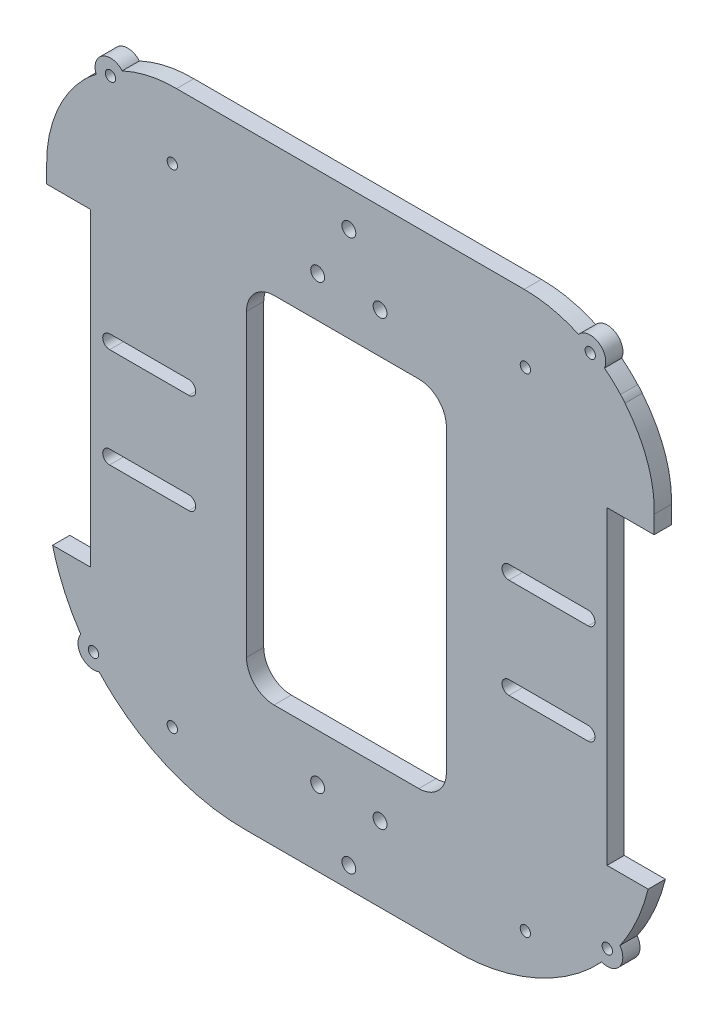
SolidWorks part; units mm, degrees
ref_plane "Front Plane" through (0, 0, 0) normal (0, 0, 1) x (1, 0, 0)
ref_plane "Top Plane" through (0, 0, 0) normal (0, 1, 0) x (1, 0, 0)
ref_plane "Right Plane" through (0, 0, 0) normal (1, 0, 0) x (0, 0, -1)
sketch "Sketch1" plane through (0, 0, 0) normal (0, 0, 1) x (1, 0, 0)
  line L0 (0.5046, 36.3194) -> (0.5046, -35.0114) construction
  line L1 (-23.6684, -1.9236) -> (30.8981, -1.9236) construction
  line L2 (47.0046, -13.9593) -> (70.0046, -13.9593) construction
  line L4 (20.8353, 50.5569) -> (-21.2253, 50.5569)
  line L6 (47.0046, -15.9593) -> (70.0046, -15.9593)
  line L7 (28.8353, 42.5569) -> (28.8353, -44.4755)
  line L10 (47.0046, -11.9593) -> (70.0046, -11.9593)
  line L13 (47.0046, 15.0407) -> (70.0046, 15.0407) construction
  line L16 (75.5046, -44.4593) -> (75.5046, 45.5407)
  line L17 (75.5046, -44.4593) -> (100.9515, -44.4593)
  line L18 (-74.4954, -44.4593) -> (-74.4954, 45.5407)
  line L19 (75.5046, 45.5407) -> (100.0597, 45.5407)
  line L21 (-74.4954, 45.5407) -> (-96.5901, 45.5407)
  line L22 (-74.4954, -44.4593) -> (-96.0698, -44.4593)
  line L23 (-45.9954, -13.9593) -> (-68.9954, -13.9593) construction
  line L24 (-45.9954, -15.9593) -> (-68.9954, -15.9593)
  line L25 (-45.9954, -11.9593) -> (-68.9954, -11.9593)
  line L26 (20.8353, -52.4755) -> (-21.2253, -52.4755)
  line L27 (-29.2253, 42.5569) -> (-29.2253, -44.4755)
  line L28 (-45.9954, 15.0407) -> (-68.9954, 15.0407) construction
  line L32 (41.4624, 99.173) -> (-37.9933, 99.173)
  line L33 (-96.0698, -44.4593) -> (-96.0698, -58.9411)
  line L34 (-57.1595, -97.8475) -> (62.0583, -97.8475)
  line L35 (100.9515, -58.9359) -> (100.9515, -44.4593)
  line L36 (-45.9954, 13.0407) -> (-68.9954, 13.0407)
  line L37 (-45.9954, 17.0407) -> (-68.9954, 17.0407)
  line L38 (47.0046, 13.0407) -> (70.0046, 13.0407)
  line L39 (47.0046, 17.0407) -> (70.0046, 17.0407)
  circle A0 centre (0.5046, -81.9236) radius 2.01
  circle A1 centre (-8.5604, -66.2225) radius 2.01
  circle A2 centre (9.5696, -66.2225) radius 2.01
  circle A3 centre (9.5696, 62.3754) radius 2.01
  circle A4 centre (-8.5604, 62.3754) radius 2.01
  circle A5 centre (0.5046, 78.0764) radius 2.01
  circle A6 centre (51.7877, 68.9682) radius 1.5
  circle A7 centre (-50.7786, 68.9682) radius 1.5
  circle A8 centre (-50.7786, -72.8153) radius 1.5
  circle A9 centre (51.7877, -72.8153) radius 1.5
  arc A18 (20.8353, 50.5569) -> (28.8353, 42.5569) centre (20.8353, 42.5569) cw
  arc A19 (28.8353, -44.4755) -> (20.8353, -52.4755) centre (20.8353, -44.4755) cw
  arc A20 (-21.2253, -52.4755) -> (-29.2253, -44.4755) centre (-21.2253, -44.4755) cw
  arc A21 (-21.2253, 50.5569) -> (-29.2253, 42.5569) centre (-21.2253, 42.5569) ccw
  arc A22 (-45.9954, -15.9593) -> (-45.9954, -11.9593) centre (-45.9954, -13.9593) ccw
  arc A23 (-68.9954, -11.9593) -> (-68.9954, -15.9593) centre (-68.9954, -13.9593) ccw
  arc A24 (-45.9954, 13.0407) -> (-45.9954, 17.0407) centre (-45.9954, 15.0407) ccw
  arc A25 (-68.9954, 17.0407) -> (-68.9954, 13.0407) centre (-68.9954, 15.0407) ccw
  arc A26 (47.0046, -15.9593) -> (47.0046, -11.9593) centre (47.0046, -13.9593) cw
  arc A27 (70.0046, -11.9593) -> (70.0046, -15.9593) centre (70.0046, -13.9593) cw
  arc A28 (47.0046, 13.0407) -> (47.0046, 17.0407) centre (47.0046, 15.0407) cw
  arc A29 (70.0046, 17.0407) -> (70.0046, 13.0407) centre (70.0046, 15.0407) cw
  spline S4 degree 3 poles (-37.9933, 99.173) (-41.8284, 99.1922) (-49.5281, 98.4356) (-60.5812, 95.0816) (-70.8089, 89.6705) (-79.8089, 82.3002) (-87.1478, 73.2755) (-92.6436, 63.0291) (-95.5634, 53.6011) (-96.4127, 47.6625) (-96.5901, 45.5407) knots 0.000115 0.000115 0.000115 0.000115 0.12506 0.250006 0.374952 0.499897 0.624843 0.749788 0.874734 0.943757 0.943757 0.943757 0.943757
  spline S5 degree 3 poles (-96.0698, -58.9411) (-96.1036, -60.2428) (-96.0208, -62.8642) (-95.2849, -67.9584) (-93.3689, -74.058) (-89.6962, -80.7285) (-84.8498, -86.585) (-79.0078, -91.4529) (-72.338, -95.1463) (-66.2226, -97.0712) (-61.1064, -97.8056) (-58.4686, -97.8842) (-57.1595, -97.8475) knots 0.000902 0.000902 0.000902 0.000902 0.063285 0.125668 0.250434 0.3752 0.499967 0.624733 0.749499 0.874265 0.936648 0.999031 0.999031 0.999031 0.999031
  spline S6 degree 3 poles (62.0583, -97.8475) (63.3493, -97.873) (65.9465, -97.7788) (71.0064, -97.0392) (77.08, -95.1471) (83.7477, -91.5254) (89.6215, -86.7311) (94.5168, -80.9234) (98.2368, -74.2556) (100.175, -68.1051) (100.9119, -62.9385) (100.9892, -60.2624) (100.9515, -58.9359) knots 0.000693 0.000693 0.000693 0.000693 0.06309 0.125486 0.250278 0.375071 0.499863 0.624656 0.749448 0.874241 0.936637 0.999033 0.999033 0.999033 0.999033
  spline S7 degree 3 poles (100.0597, 45.5407) (100.0418, 45.7543) (99.85, 47.8935) (98.9687, 53.8304) (96.1308, 63.0673) (90.671, 73.2777) (83.3411, 82.2625) (74.3661, 89.5939) (64.1648, 95.0502) (54.9283, 97.8853) (47.2878, 99.0202) (43.4004, 99.1912) (41.4624, 99.173) knots 0.055789 0.055789 0.055789 0.055789 0.062711 0.125183 0.250126 0.37507 0.500013 0.624957 0.7499 0.874844 0.937315 0.999787 0.999787 0.999787 0.999787
  point P11 (0.1732, 0.5407)
  point P12 (0.492, 0.5407)
  point P13 (0.1732, 0.5407)
  point P27 (58.5046, -13.9593)
  point P43 (1.739, 0.6627)
  point P45 (-57.4954, -13.9593)
  point P49 (58.5046, 15.0407)
  point P83 (-57.4954, 15.0407)
  dimension "D1" = 4.02
  dimension "D2" = 4.02
  dimension "D3" = 4.02
  dimension "D10" = 3
  dimension "D12" = 8
  dimension "D9" = 160
  dimension "D13" = 150
  dimension "D4" = 18.13
  dimension "D5" = 18.13
  dimension "D6" = 18.13
  dimension "D7" = 0
  dimension "D8" = 0
  dimension "D11" = 0
  dimension "D14" = 4
  dimension "D15" = 23
  dimension "D16" = 4
  dimension "D17" = 29
  dimension "D18" = 12.0358
  dimension "D19" = 23
  dimension "D20" = 17
  dimension "D21" = 17
extrude "Boss-Extrude1" add sketch "Sketch1" along normal blind 5
extrude "Cut-Extrude1" cut sketch "Sketch3" against normal blind 5
sketch "Sketch3" plane through (-67.7257, -284.0675, 0) normal (0, 0, -1) x (0, -1, 0)
  circle A0 centre (-358.5123, 8.0352) radius 1.5021
  circle A1 centre (-358.5123, -146.9648) radius 1.5021
  circle A2 centre (-198.5123, -146.9648) radius 1.5
  circle A3 centre (-198.5123, 8.0352) radius 1.5
sketch "Sketch6" plane through (0, 0, 5) normal (0, 0, 1) x (1, 0, 0)
  line L0 (-49.5429, 88.4331) -> (51.4414, 88.4331)
  line L1 (89.1759, 50.6989) -> (89.1759, -30.4257)
  line L2 (31.5812, -88.02) -> (-29.6827, -88.02)
  line L3 (-87.2774, -30.4257) -> (-87.2774, 50.6989)
  arc A0 (74.7752, 80.2875) -> (67.2334, 84.9859) centre (70.6261, 82.0297) ccw
  arc A1 (73.9299, -69.5438) -> (79.2529, -62.7505) centre (75.5867, -65.3599) ccw
  arc A2 (-77.3839, -62.7925) -> (-72.0309, -69.5437) centre (-73.6882, -65.3599) ccw
  arc A3 (-65.3408, 84.9927) -> (-72.9088, 80.3661) centre (-68.7276, 82.0297) ccw
  circle A4 centre (-68.7276, 82.0297) radius 1.5
  circle A5 centre (70.6261, 82.0297) radius 1.5
  circle A6 centre (75.5867, -65.3599) radius 1.4965
  circle A7 centre (-73.6882, -65.3599) radius 1.5
  circle A8 centre (0, 0) radius 127.3889
  spline S0 degree 2 poles (-65.3408, 84.9927) (-57.7881, 88.4937) (-49.5429, 88.4331) knots 0 0 0 1 1 1
  spline S1 degree 2 poles (51.4414, 88.4331) (59.6785, 88.4372) (67.2334, 84.9859) knots 0 0 0 1 1 1
  spline S2 degree 3 poles (74.7752, 80.2875) (83.589, 73.3085) (89.6688, 62.0975) (89.1759, 50.6989) knots 0 0 0 0 1 1 1 1
  spline S3 degree 3 poles (89.1759, -30.4257) (89.1783, -41.8551) (85.7624, -53.3425) (79.2529, -62.7505) knots 0 0 0 0 1 1 1 1
  spline S4 degree 3 poles (73.9299, -69.5438) (69.4345, -74.4862) (56.5188, -84.0244) (40.8074, -88.1323) (31.5812, -88.02) knots 0 0 0 0 0.421408 1 1 1 1
  spline S5 degree 3 poles (-29.6827, -88.02) (-45.5108, -88.0933) (-61.3333, -81.2731) (-72.0309, -69.5437) knots 0 0 0 0 1 1 1 1
  spline S6 degree 3 poles (-77.3839, -62.7925) (-83.8133, -53.3218) (-87.3231, -41.8758) (-87.2774, -30.4257) knots 0 0 0 0 1 1 1 1
  spline S7 degree 3 poles (-87.2774, 50.6989) (-87.3453, 62.0926) (-81.9185, 73.4085) (-72.9088, 80.3661) knots 0 0 0 0 1 1 1 1
extrude "Cut-Extrude2" cut sketch "Sketch6" against normal blind 10 contours A8 L3 S7 A3 S0 L0 S1 A0 S2 L1 S3 A1 S4 L2 S5 A2 S6
sketch "Sketch7" plane through (0, 0, 5) normal (0, 0, 1) x (1, 0, 0)
  circle A0 centre (75.5867, -65.3599) radius 1.5
  circle A1 centre (-73.6882, -65.3599) radius 1.5
  circle A2 centre (70.6261, 82.0297) radius 1.5
  circle A3 centre (-68.7276, 82.0297) radius 1.5
  dimension "D1" = 3
  dimension "D2" = 3
  dimension "D3" = 3
  dimension "D4" = 3
extrude "Cut-Extrude3" cut sketch "Sketch7" against normal blind 10
sketch "Sketch8" plane through (0, 0, 5) normal (0, 0, 1) x (1, 0, 0)
  arc A0 (79.4255, 75.9353) -> (80.7408, 74.4112) centre (79.239, 74.4448) ccw
  circle A1 centre (-75.761, 74.4448) radius 1.5021
  spline S0 degree 2 poles (80.7408, 74.4112) (80.2044, 75.2781) (79.4255, 75.9353) knots 0 0 0 1 1 1
extrude "Boss-Extrude2" add sketch "Sketch8" against normal blind 5
